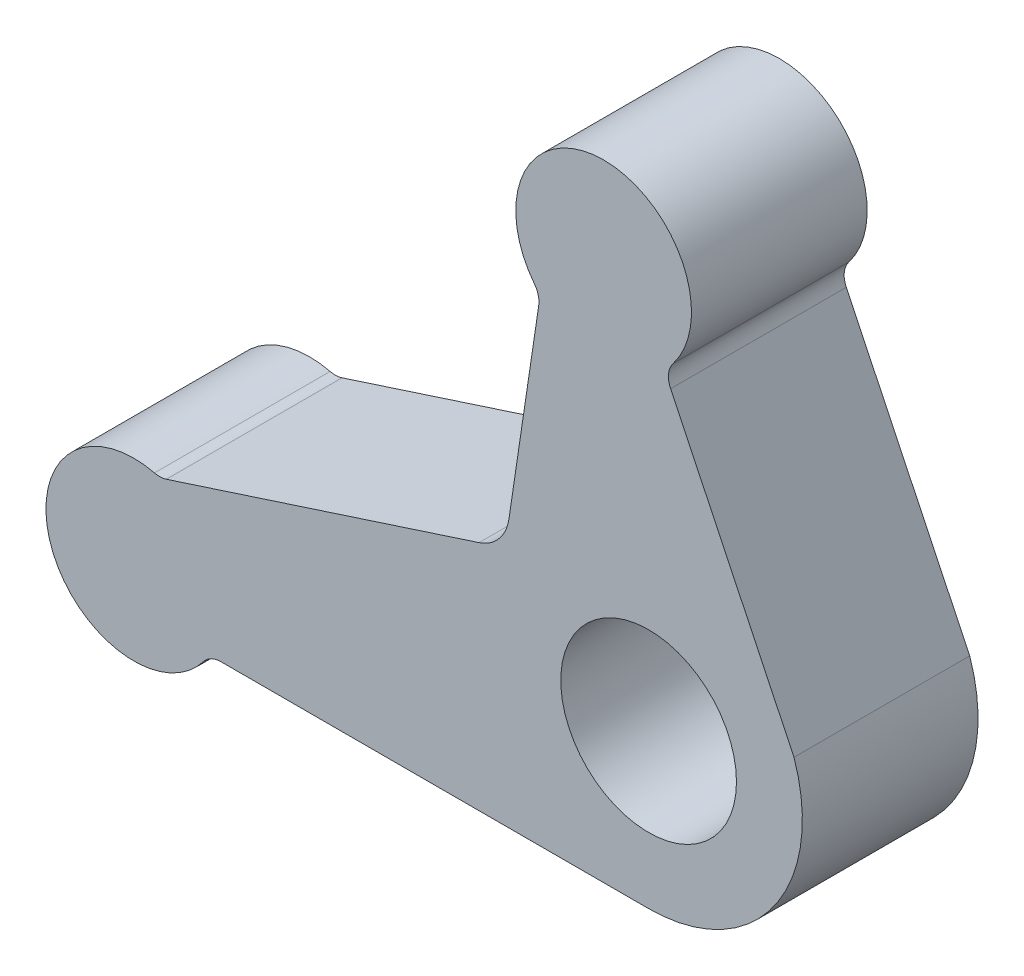
SolidWorks part; units mm, degrees
ref_plane "Plane1" through (0, 0, 0) normal (0, 0, 1) x (1, 0, 0)
ref_plane "Plane2" through (0, 0, 0) normal (0, 1, 0) x (1, 0, 0)
ref_plane "Plane3" through (0, 0, 0) normal (1, 0, 0) x (0, 0, -1)
sketch "Esquisse1" plane through (0, 0, 0) normal (0, 0, 1) x (1, 0, 0)
  line L0 (0, -3.5) -> (-9.7358, -3.5)
  line L1 (3.3096, 1.1386) -> (0.5, 7)
  line L2 (-10.9785, -0.524) -> (-3.8603, 1.7856)
  line L3 (-3.1799, 2.5894) -> (-2.5017, 7.1391)
  arc A0 (0, -3.5) -> (3.3096, 1.1386) centre (0, 0) ccw
  arc A1 (-3.1799, 2.5894) -> (-3.8603, 1.7856) centre (-4.1689, 2.7368) cw
  arc A2 (0.5559, 7.5227) -> (-2.6018, 7.5201) centre (-1.024, 8.7491) ccw
  arc A3 (-11.2502, -0.5344) -> (-10.1325, -3.6957) centre (-11.7195, -2.4786) ccw
  arc A4 (-11.2502, -0.5344) -> (-10.9785, -0.524) centre (-11.1328, -0.0484) ccw
  arc A5 (-9.7358, -3.5) -> (-10.1325, -3.6957) centre (-9.7358, -4) ccw
  arc A6 (-2.6018, 7.5201) -> (-2.5017, 7.1391) centre (-2.9963, 7.2128) cw
  arc A7 (0.5559, 7.5227) -> (0.5, 7) centre (0.9509, 7.2161) ccw
  circle A8 centre (0, 0) radius 2
  dimension "D1" = 7
  dimension "D3" = 4
  dimension "D4" = 4
  dimension "D5" = 1
  dimension "D6" = 0.5
  dimension "D2" = 0.5
  dimension "D7" = 0.5
  dimension "D8" = 0.5
  dimension "D9" = 4
  dimension "D10" = 6.5
  dimension "D11" = 4.6
extrude "levier" add sketch "Esquisse1" along normal blind 4
